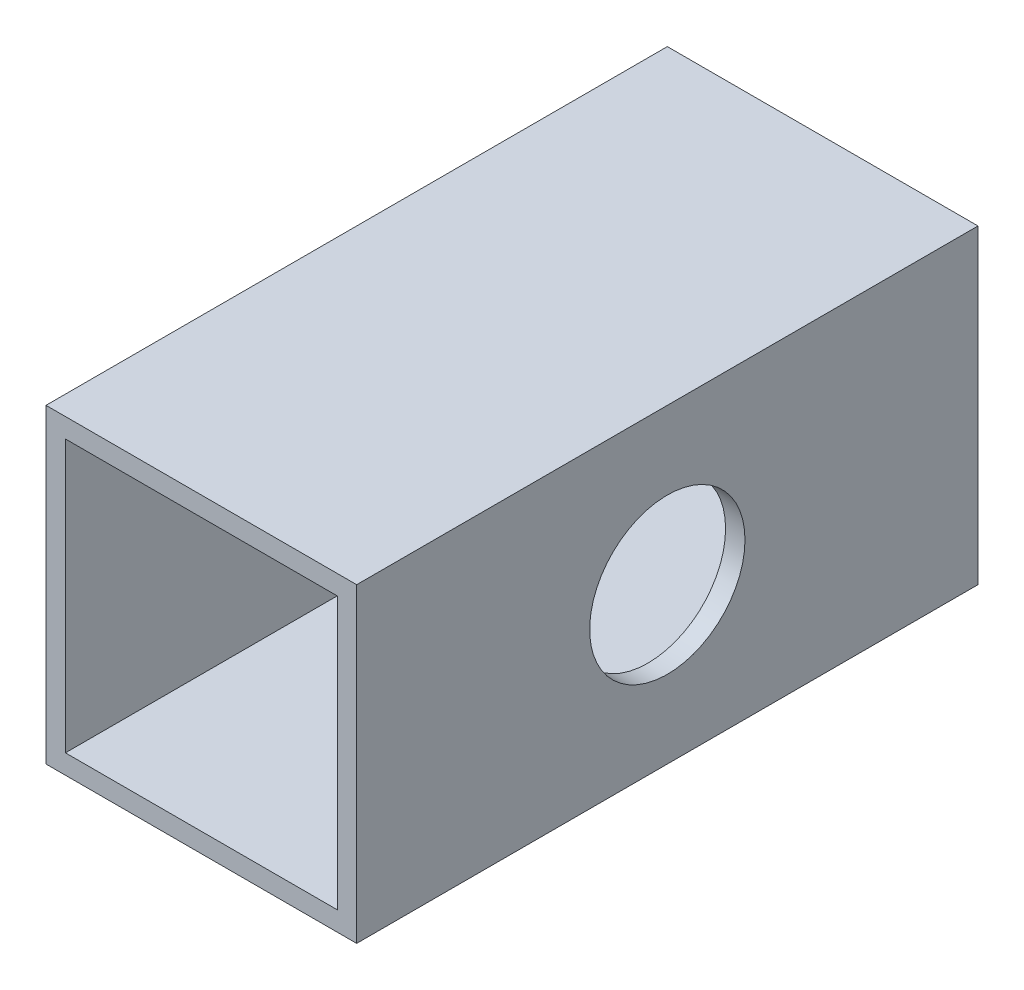
SolidWorks part; units mm, degrees
material "6063-T6"
ref_plane "Front Plane" through (0, 0, 0) normal (0, 0, 1) x (1, 0, 0)
ref_plane "Top Plane" through (0, 0, 0) normal (0, 1, 0) x (1, 0, 0)
ref_plane "Right Plane" through (0, 0, 0) normal (1, 0, 0) x (0, 0, -1)
sketch "Sketch1" plane through (0, 0, 0) normal (0, 0, 1) x (1, 0, 0)
  line L1 (-12.7, -12.7) -> (12.7, -12.7)
  line L2 (-12.7, -12.7) -> (-12.7, 12.7)
  line L3 (-12.7, 12.7) -> (12.7, 12.7)
  line L4 (12.7, -12.7) -> (12.7, 12.7)
  line L5 (-12.7, -12.7) -> (12.7, 12.7) construction
  line L6 (-12.7, 12.7) -> (12.7, -12.7) construction
  line L7 (-11.1125, -11.1125) -> (11.1125, -11.1125)
  line L8 (-11.1125, -11.1125) -> (-11.1125, 11.1125)
  line L9 (-11.1125, 11.1125) -> (11.1125, 11.1125)
  line L10 (11.1125, -11.1125) -> (11.1125, 11.1125)
  line L11 (-11.1125, -11.1125) -> (11.1125, 11.1125) construction
  line L12 (-11.1125, 11.1125) -> (11.1125, -11.1125) construction
  point P0 (0, 0)
  point P6 (0, 0)
  dimension "D1" = 25.4
  dimension "D2" = 22.225
extrude "Boss-Extrude1" add sketch "Sketch1" along normal blind 50.8
sketch "Sketch2" plane through (12.7, 0, 0) normal (1, 0, 0) x (0, 0, -1)
  line L0 (-50.8, 12.7) -> (0, -12.7) construction
  line L1 (0, 12.7) -> (-50.8, -12.7) construction
  circle A0 centre (-25.4, 0) radius 6.35
  dimension "D1" = 12.7
extrude "Cut-Extrude2" cut sketch "Sketch2" against normal through all
